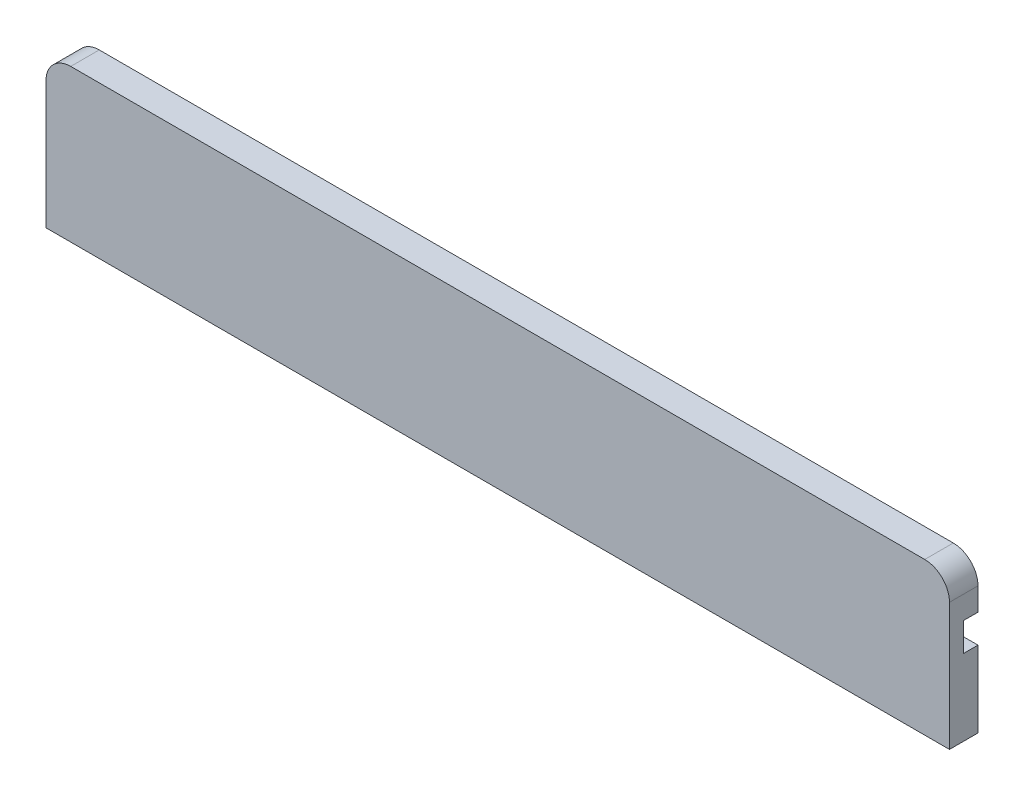
SolidWorks part; units mm, degrees
ref_plane "Front" through (0, 0, 0) normal (0, 0, 1) x (1, 0, 0)
ref_plane "Top" through (0, 0, 0) normal (0, 1, 0) x (1, 0, 0)
ref_plane "Right" through (0, 0, 0) normal (1, 0, 0) x (0, 0, -1)
sketch "Sketch1" plane through (0, 0, 0) normal (0, 0, 1) x (1, 0, 0)
  line L0 (301.625, 101.6) -> (301.625, 0)
  line L1 (301.625, 101.6) -> (-301.625, 101.6)
  line L2 (301.625, 0) -> (-301.625, 0)
  line L3 (-301.625, 101.6) -> (-301.625, 0)
  line L4 (301.625, 101.6) -> (-301.625, 0) construction
  line L5 (301.625, 0) -> (-301.625, 101.6) construction
  line L6 (0, 50.8) -> (0, 0) construction
  point P1 (0, 50.8)
  dimension "D1" = 101.6
  dimension "D2" = 603.25
extrude "Boss-Extrude1" add sketch "Sketch1" along normal blind 19.05
sketch "Sketch2" plane through (301.625, 0, 0) normal (1, 0, 0) x (0, 0, -1)
  line L0 (0, 0) -> (0, 101.6) construction
  line L1 (0, 69.85) -> (-9.525, 69.85)
  line L2 (0, 69.85) -> (0, 50.8)
  line L3 (0, 50.8) -> (-9.525, 50.8)
  line L4 (-9.525, 69.85) -> (-9.525, 50.8)
  line L5 (-19.05, 0) -> (0, 0) construction
  dimension "D1" = 19.05
  dimension "D2" = 9.525
  dimension "D3" = 50.8
extrude "Cut-Extrude1" cut sketch "Sketch2" against normal through all
fillet "Fillet1" radius 16.51 2 edges at (-301.625, 101.6, 9.525) (301.625, 101.6, 9.525)
